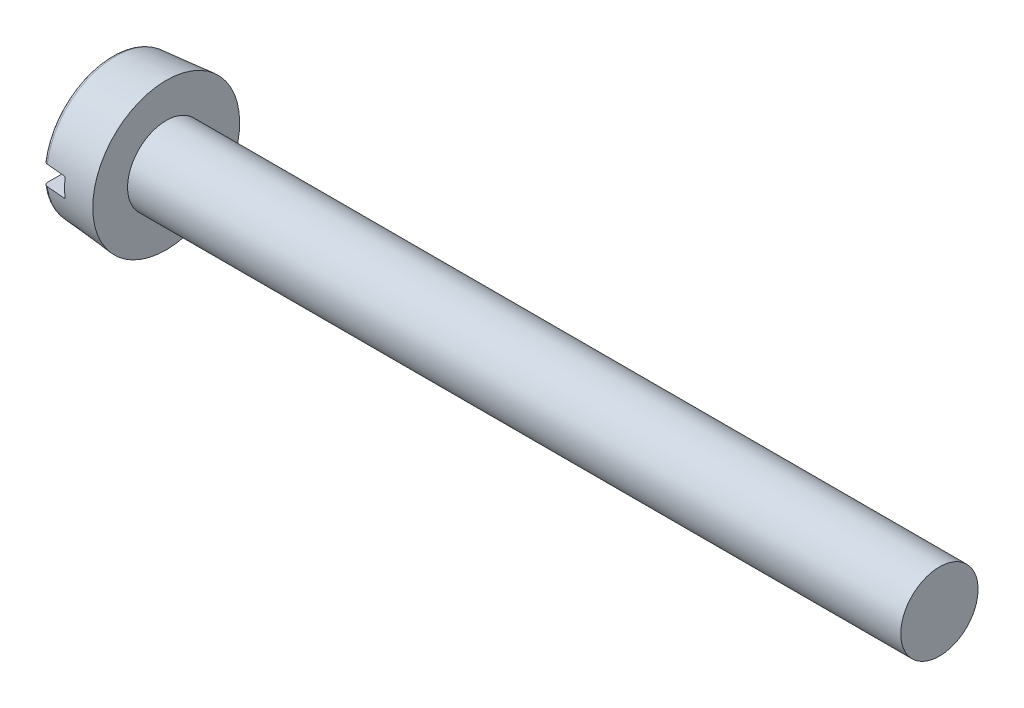
SolidWorks part; units mm, degrees
ref_plane "Plane1" through (0, 0, 0) normal (0, 0, 1) x (1, 0, 0)
ref_plane "Plane2" through (0, 0, 0) normal (0, 1, 0) x (1, 0, 0)
ref_plane "Plane3" through (0, 0, 0) normal (1, 0, 0) x (0, 0, -1)
sketch "BodySke" plane through (0, 0, 0) normal (0, 0, 1) x (1, 0, 0)
  line L0 (1.4, 1) -> (1.4, 1.9)
  line L1 (0, 0) -> (0, 1.7775)
  line L2 (-25.4, 0) -> (127, 0) construction
  line L3 (21.4, 0) -> (0, 0)
  line L4 (1.4, 1) -> (21.4, 1)
  line L5 (21.4, 1) -> (21.4, 0)
  line L6 (0, 1.7775) -> (1.4, 1.9)
  line L9 (1.8, 2.5875) -> (1.8, -6.9375) construction
  line L10 (1.4, 6.35) -> (1.4, -3.175) construction
  dimension "Length" = 20
  dimension "Head_ht" = 1.4
  dimension "Advance" = 0.4
  dimension "Thread_nom" = 20
  dimension "Head_dia" = 3.8
  dimension "Head_side_angle" = 5
  dimension "Diameter" = 2
revolve "Base-Revolve" add sketch "BodySke"
cosmetic thread "ThreadCosmetic" [suppressed]
fillet "Fillet1" [suppressed] radius 0.1
fillet "Fillet2" radius 0.1 1 edges at (0, 0, 1.7775)
sketch "Sketch2" plane through (0, 0, 0) normal (1, 0, 0) x (0, 0, -1)
  line L0 (1.9, -0.25) -> (-1.9, -0.25)
  line L1 (1.9, -0.25) -> (1.9, 0.25)
  line L2 (-1.9, 0.25) -> (1.9, 0.25)
  line L3 (-1.9, 0.25) -> (-1.9, -0.25)
  dimension "D1" = 3.8
  dimension "Slot_width" = 0.5
  dimension "D2" = 1.9
  dimension "D3" = 0.25
extrude "Slot" cut sketch "Sketch2" along normal blind 0.6
sketch "ThdSchSke" plane through (0, 0, 0) normal (0, 0, 1) x (1, 0, 0)
  line L0 (2.2, -0.774) -> (2.0418, -1)
  line L1 (2.2, -0.774) -> (2.3582, -1)
  line L2 (2.3582, -1) -> (2.3582, -1.25)
  line L3 (-3.175, 0) -> (5.1513, 0) construction
  line L5 (2.3582, -1.25) -> (2.0418, -1.25)
  line L6 (2.0418, -1.25) -> (2.0418, -1)
  dimension "Diameter" = 2
  dimension "SideAngle" = 55
  dimension "VeeAngle" = 70
  dimension "Thread_minor" = 1.548
  dimension "Overcut" = 2.5
  dimension "Start" = 2.2
revolve "ThreadSchematic" [suppressed] cut sketch "ThdSchSke" angle 360 about L3
pattern_linear "ThdSchPat" [suppressed]
equation "\"D1@Sketch2\" = \"Head_dia@BodySke\""
equation "\"D2@Sketch2\" = \"D1@Sketch2\" / 2"
equation "\"D3@Sketch2\" = \"Slot_width@Sketch2\" / 2"
equation "\"Thread_length@ThreadCosmetic\" = ((sgn( (\"Length@BodySke\" - \"Advance@BodySke\" * 2.0 ) - \"Thread_nom@BodySke\" )-1)*( (\"Length@BodySke\" - \"Advance@BodySke\"  * 2.0) - \"Thread_nom@BodySke\" ))/-2+ \"Thread_nom@BodySke\""
equation "\"Thread_minor@ThdSchSke\" = \"Thread_minor@ThreadCosmetic\""
equation "\"Diameter@ThdSchSke\" = \"Diameter@BodySke\""
equation "\"Overcut@ThdSchSke\" = \"Diameter@BodySke\" * 1.25"
equation "\"Start@ThdSchSke\" = \"Head_ht@BodySke\" + \"Length@BodySke\" - \"Thread_length@ThreadCosmetic\"  '---Non-countersunk---"
equation "\"Num_threads@ThdSchPat\" = int( \"Thread_length@ThreadCosmetic\" / \"Advance@BodySke\" + 0.999 )  + 1"
equation "\"Advance@ThdSchPat\" = \"Thread_length@ThreadCosmetic\" /  (\"Num_threads@ThdSchPat\" - 1) 'relax it"
